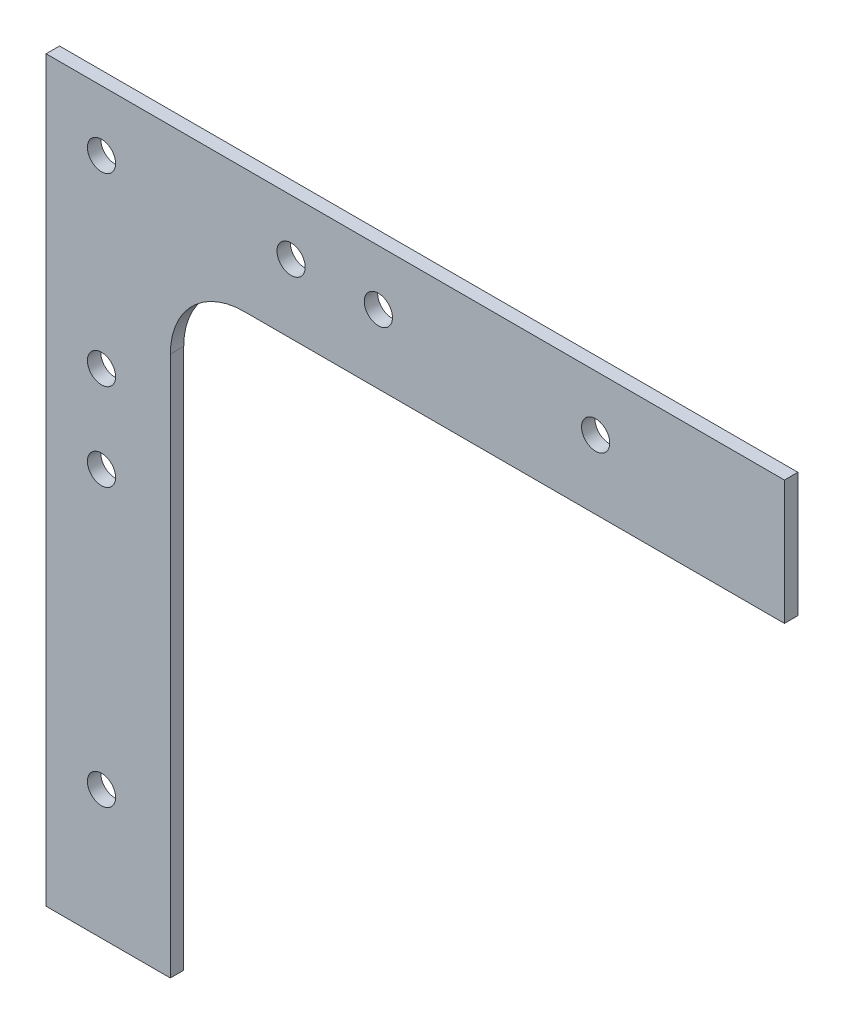
SolidWorks part; units mm, degrees
ref_plane "Front Plane" through (0, 0, 0) normal (0, 0, 1) x (1, 0, 0)
ref_plane "Top Plane" through (0, 0, 0) normal (0, 1, 0) x (1, 0, 0)
ref_plane "Right Plane" through (0, 0, 0) normal (1, 0, 0) x (0, 0, -1)
sketch "Sketch1" plane through (0, 0, 0) normal (0, 0, 1) x (1, 0, 0)
  line L0 (0, 0) -> (0, -127)
  line L1 (0, 0) -> (127, 0)
  line L2 (127, 0) -> (127, -21.3614)
  line L3 (127, -21.3614) -> (21.3614, -21.3614)
  line L4 (0, -127) -> (21.3614, -127)
  line L5 (21.3614, -127) -> (21.3614, -21.3614)
  dimension "D1" = 127
  dimension "D2" = 127
  dimension "D3" = 21.3614
  dimension "D4" = 21.3614
extrude "Boss-Extrude1" add sketch "Sketch1" along normal blind 2.3114
fillet "Fillet1" radius 12.7 1 edges at (21.3614, -21.3614, 1.1557)
sketch "Sketch2" plane through (0, 0, 2.3114) normal (0, 0, 1) x (1, 0, 0)
  circle A0 centre (9.525, -104.8309) radius 2.4257
  circle A1 centre (94.5261, -9.525) radius 2.4257
extrude "Cut-Extrude1" cut sketch "Sketch2" against normal through all
sketch "Sketch3" plane through (0, 0, 2.3114) normal (0, 0, 1) x (1, 0, 0)
  circle A0 centre (42.1386, -9.525) radius 2.4257
  circle A1 centre (42.1386, -9.525) radius 2.4257 construction
  circle A2 centre (9.525, -10.3886) radius 2.4257
  circle A3 centre (9.525, -10.3886) radius 2.4257 construction
extrude "Cut-Extrude2" cut sketch "Sketch3" against normal through all
sketch "Sketch4" plane through (0, 0, 2.3114) normal (0, 0, 1) x (1, 0, 0)
  circle A0 centre (9.525, -42.1386) radius 2.4257
  circle A1 centre (9.525, -42.1386) radius 2.4257 construction
extrude "Cut-Extrude3" cut sketch "Sketch4" against normal through all
sketch "Sketch5" plane through (0, 0, 2.3114) normal (0, 0, 1) x (1, 0, 0)
  circle A0 centre (9.525, -57.15) radius 2.4257
  circle A1 centre (9.525, -57.15) radius 2.4257 construction
extrude "Cut-Extrude4" cut sketch "Sketch5" against normal through all
sketch "Sketch6" plane through (0, 0, 2.3114) normal (0, 0, 1) x (1, 0, 0)
  line L0 (94.5261, -9.525) -> (57.15, -9.525) construction
  line L1 (0, 0) -> (0, -127) construction
  circle A0 centre (57.15, -9.525) radius 2.4257
  circle A1 centre (94.5261, -9.525) radius 2.4257 construction
  dimension "D1" = 57.15
extrude "Cut-Extrude5" cut sketch "Sketch6" against normal through all
